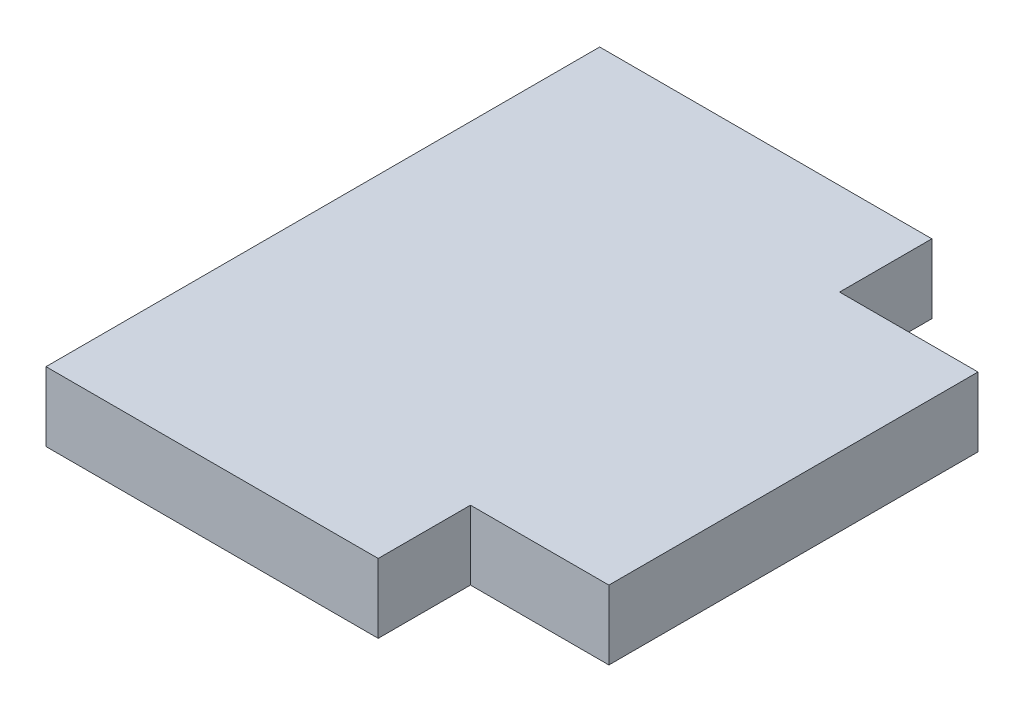
SolidWorks part; units mm, degrees
ref_plane "Спереди" through (0, 0, 0) normal (0, 0, 1) x (1, 0, 0)
ref_plane "Сверху" through (0, 0, 0) normal (0, 1, 0) x (1, 0, 0)
ref_plane "Справа" through (0, 0, 0) normal (1, 0, 0) x (0, 0, -1)
sketch "Эскиз1" plane through (0, 0, 0) normal (0, 1, 0) x (1, 0, 0)
  line L1 (0, 0) -> (10.2, 0)
  line L2 (0, 0) -> (0, 12)
  line L3 (0, 12) -> (10.2, 12)
  line L4 (10.2, 0) -> (10.2, 12)
  dimension "D1" = 10.2
  dimension "D2" = 12
extrude "Бобышка-Вытянуть1" add sketch "Эскиз1" along normal blind 1.5
sketch "Эскиз2" plane through (0, 1.5, 0) normal (0, 1, 0) x (1, 0, 0)
  line L0 (10.2, 6) -> (0, 6) construction
  line L1 (10.2, 0) -> (10.2, 12) construction
  line L2 (0, 12) -> (0, 0) construction
  line L3 (10.2, 12) -> (0, 12) construction
  line L4 (7.2, 12) -> (10.2, 12)
  line L5 (7.2, 12) -> (7.2, 10)
  line L6 (7.2, 10) -> (10.2, 10)
  line L7 (10.2, 12) -> (10.2, 10)
  line L8 (7.2, 2) -> (10.2, 2)
  line L9 (7.2, 0) -> (7.2, 2)
  line L10 (7.2, 0) -> (10.2, 0)
  line L11 (10.2, 0) -> (10.2, 2)
  dimension "D1" = 3
  dimension "D2" = 2
extrude "Вырез-Вытянуть1" cut sketch "Эскиз2" against normal through all
